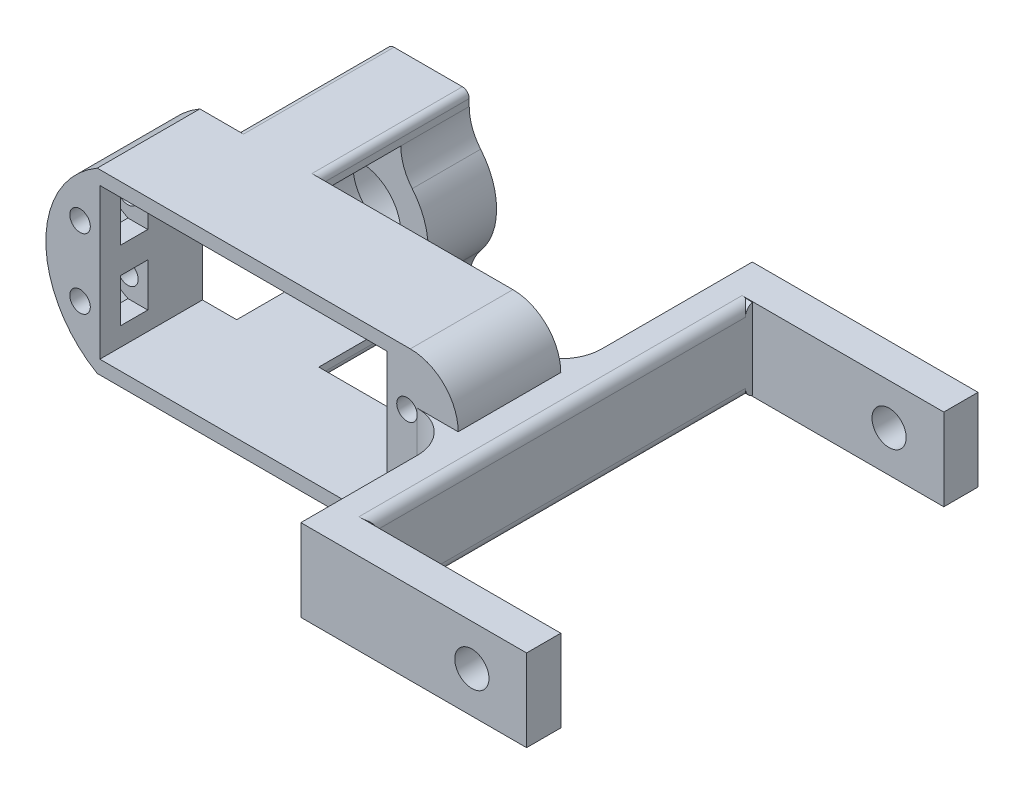
SolidWorks part; units mm, degrees
ref_plane "Plan de face" through (0, 0, 0) normal (0, 0, 1) x (1, 0, 0)
ref_plane "Plan de dessus" through (0, 0, 0) normal (0, 1, 0) x (1, 0, 0)
ref_plane "Plan de droite" through (0, 0, 0) normal (1, 0, 0) x (0, 0, -1)
sketch "Esquisse1" plane through (0, 0, 0) normal (0, 0, 1) x (1, 0, 0)
  line L1 (-23.2387, 9.5601) -> (56.7613, 9.5601)
  line L2 (-23.2387, 9.5601) -> (-23.2387, -16.4399)
  line L3 (-23.2387, -16.4399) -> (56.7613, -16.4399)
  line L4 (56.7613, 9.5601) -> (56.7613, -16.4399)
  dimension "D1" = 26
  dimension "D2" = 80
extrude "Boss.-Extru.1" add sketch "Esquisse1" along normal blind 5
sketch "Esquisse4" plane through (0, 0, 0) normal (0, 0, -1) x (-1, 0, 0)
  line L0 (23.2387, 9.5601) -> (23.2387, -16.4399) construction
  line L1 (38.2387, -13.9399) -> (23.2387, -13.9399)
  line L2 (38.2387, -13.9399) -> (38.2387, 7.0601)
  line L3 (38.2387, 7.0601) -> (23.2387, 7.0601)
  line L4 (23.2387, -13.9399) -> (23.2387, 7.0601)
  line L5 (23.2387, -16.4399) -> (-56.7613, -16.4399) construction
  line L6 (-56.7613, 9.5601) -> (23.2387, 9.5601) construction
  dimension "D1" = 0
  dimension "D2" = 2.5
  dimension "D3" = 2.5
  dimension "D4" = 15
extrude "Boss.-Extru.2" add sketch "Esquisse4" against normal blind 23
sketch "Esquisse6" plane through (0, -13.9399, 0) normal (0, -1, 0) x (1, 0, 0)
  line L0 (-23.2387, 23) -> (-23.2387, 5) construction
  line L1 (-23.2387, 0) -> (-38.2387, 0) construction
  circle A0 centre (-28.7387, 5) radius 1.9
  dimension "D2" = 5
  dimension "D3" = 3.8
  dimension "D1" = 5.5
extrude "Enlèv. mat.-Extru.1" cut sketch "Esquisse6" against normal blind 23
sketch "Esquisse7" plane through (0, 0, 23) normal (0, 0, 1) x (1, 0, 0)
  line L0 (-23.2387, 7.0601) -> (-23.2387, -13.9399) construction
  line L1 (-38.2387, 7.0601) -> (-23.2387, 7.0601) construction
  circle A0 centre (-33.2387, -3.4399) radius 2.5
  dimension "D1" = 5
  dimension "D2" = 10
  dimension "D3" = 10.5
extrude "Enlèv. mat.-Extru.2" cut sketch "Esquisse7" against normal blind 33
sketch "Esquisse8" plane through (0, 0, 0) normal (0, 0, -1) x (-1, 0, 0)
  line L0 (23.2387, -13.9399) -> (38.2387, -13.9399) construction
  line L1 (50.0831, -10.9399) -> (26.2387, -10.9399)
  line L2 (50.0831, -10.9399) -> (50.0831, 4.0601)
  line L3 (50.0831, 4.0601) -> (26.2387, 4.0601)
  line L4 (26.2387, -10.9399) -> (26.2387, 4.0601)
  line L5 (38.2387, 7.0601) -> (23.2387, 7.0601) construction
  line L6 (23.2387, -13.9399) -> (23.2387, -16.4399) construction
  dimension "D1" = 3
  dimension "D2" = 3
  dimension "D3" = 3
extrude "Enlèv. mat.-Extru.3" cut sketch "Esquisse8" against normal blind 20
sketch "Esquisse9" plane through (0, 0, 0) normal (0, 0, -1) x (-1, 0, 0)
  line L19 (38.2387, -13.9399) -> (38.2387, -10.9399)
  line L20 (38.2387, -10.9399) -> (26.2387, -10.9399)
  line L21 (26.2387, -10.9399) -> (26.2387, 4.0601)
  line L22 (26.2387, 4.0601) -> (38.2387, 4.0601)
  line L23 (38.2387, 4.0601) -> (38.2387, 7.0601)
  line L24 (38.2387, 7.0601) -> (23.2387, 7.0601)
  line L25 (23.2387, 7.0601) -> (23.2387, 9.5601)
  line L26 (23.2387, 9.5601) -> (-56.7613, 9.5601)
  line L27 (-56.7613, 9.5601) -> (-56.7613, -16.4399)
  line L28 (-56.7613, -16.4399) -> (23.2387, -16.4399)
  line L29 (23.2387, -16.4399) -> (23.2387, -13.9399)
  line L30 (23.2387, -13.9399) -> (38.2387, -13.9399)
  line L37 (23.2387, 7.0601) -> (23.2387, 9.5601)
  line L38 (23.2387, 9.5601) -> (17.8135, 9.5601)
  line L40 (17.8135, -16.4399) -> (23.2387, -16.4399)
  line L41 (23.2387, -16.4399) -> (23.2387, -13.9399)
  arc A3 (17.8135, -16.4399) -> (23.2387, -13.9399) centre (17.8135, -9.3033) ccw
  arc A4 (17.8135, 9.5601) -> (23.2387, 7.0601) centre (17.8135, 2.4236) cw
  dimension "D1" = 0
extrude "Enlèv. mat.-Extru.4" cut sketch "Esquisse9" against normal blind 20
sketch "Esquisse10" plane through (0, -13.9399, 0) normal (0, -1, 0) x (1, 0, 0)
  line L5 (-38.2387, 0) -> (-23.2387, 0)
  line L6 (-23.2387, 0) -> (-23.2387, 5)
  line L7 (-23.2387, 5) -> (-23.2387, 23)
  line L8 (-23.2387, 23) -> (-38.2387, 23)
  line L9 (-38.2387, 23) -> (-38.2387, 0)
  line L12 (-23.2387, 21.5) -> (-23.2387, 23)
  line L13 (-23.2387, 23) -> (-24.7387, 23)
  arc A0 (-23.2387, 21.5) -> (-24.7387, 23) centre (-24.7387, 21.5) ccw
  dimension "D2" = 3
  dimension "D1" = 0
extrude "Enlèv. mat.-Extru.5" cut sketch "Esquisse10" against normal blind 25
sketch "Esquisse12" plane through (0, -13.9399, 0) normal (0, -1, 0) x (1, 0, 0)
  line L0 (-24.7387, 23) -> (-38.2387, 23) construction
  line L1 (-38.2387, 23) -> (-36.7387, 23)
  line L2 (-38.2387, 23) -> (-38.2387, 21.5)
  arc A0 (-36.7387, 23) -> (-38.2387, 21.5) centre (-36.7387, 21.5) ccw
  dimension "D1" = 3
  dimension "D3" = 1.5
extrude "Enlèv. mat.-Extru.7" cut sketch "Esquisse12" against normal blind 25
sketch "Esquisse13" plane through (0, 7.0601, 0) normal (0, 1, 0) x (1, 0, 0)
  line L1 (-30.7594, -1.5) -> (-32.7801, -5)
  line L2 (-32.7801, -5) -> (-30.7594, -8.5)
  line L3 (-30.7594, -8.5) -> (-26.718, -8.5)
  line L4 (-26.718, -8.5) -> (-24.6972, -5)
  line L5 (-24.6972, -5) -> (-26.718, -1.5)
  line L6 (-26.718, -1.5) -> (-30.7594, -1.5)
  circle A0 centre (-28.7387, -5) radius 3.5 construction
  circle A1 centre (-28.7387, -5) radius 1.9 construction
  dimension "D1" = 7
extrude "Enlèv. mat.-Extru.8" cut sketch "Esquisse13" against normal blind 1
sketch "Esquisse14" plane through (0, 7.0601, 0) normal (0, 1, 0) x (1, 0, 0)
  line L0 (-30.7594, -1.5) -> (-32.7801, -5) construction
  line L1 (-26.718, -1.5) -> (-30.7594, -1.5) construction
  line L2 (-24.6972, -5) -> (-26.718, -1.5) construction
  line L3 (-26.718, -8.5) -> (-24.6972, -5) construction
  line L4 (-30.7594, -8.5) -> (-26.718, -8.5) construction
  line L6 (-25.8519, 0) -> (-31.6254, 0)
  line L7 (-31.6254, 0) -> (-34.5122, -5)
  line L8 (-34.5122, -5) -> (-31.6254, -10)
  line L9 (-31.6254, -10) -> (-25.8519, -10)
  line L15 (-32.7801, -5) -> (-30.7594, -8.5) construction
  line L16 (-30.7594, -1.5) -> (-32.7801, -5)
  line L17 (-26.718, -1.5) -> (-30.7594, -1.5)
  line L18 (-24.6972, -5) -> (-26.718, -1.5)
  line L19 (-26.718, -8.5) -> (-24.6972, -5)
  line L20 (-30.7594, -8.5) -> (-26.718, -8.5)
  line L21 (-32.7801, -5) -> (-30.7594, -8.5)
  line L22 (-25.8519, -10) -> (-23.2387, -5.4737)
  line L27 (-23.2387, -4.5263) -> (-25.8519, 0)
  line L28 (-38.2387, 0) -> (-23.2387, 0) construction
  line L29 (-23.2387, -4.5263) -> (-23.2387, -5.4737)
  line L30 (-23.2387, -21.5) -> (-23.2387, -5) construction
  circle A1 centre (-28.7387, -5) radius 5 construction
  circle A2 centre (-28.7387, -5) radius 1.9 construction
extrude "Boss.-Extru.3" add sketch "Esquisse14" along normal blind 2
sketch "Esquisse15" plane through (0, 0, 0) normal (0, 0, -1) x (-1, 0, 0)
  circle A7 centre (-51.7613, -8.5399) radius 1.5
  circle A8 centre (-51.7613, 1.6601) radius 1.5
  circle A9 centre (-3.9613, -8.5399) radius 1.5
  circle A10 centre (-3.9613, 1.6601) radius 1.5
  dimension "D10" = 3
extrude "Enlèv. mat.-Extru.9" cut sketch "Esquisse15" against normal blind 19
sketch "Esquisse16" plane through (0, 0, 0) normal (0, 0, -1) x (-1, 0, 0)
  line L0 (17.8135, -16.4399) -> (-56.7613, -16.4399) construction
  line L1 (-56.7613, -16.4399) -> (-56.7613, 9.5601) construction
  line L2 (-43.3764, 11.4729) -> (-43.3764, 11.5601)
  line L3 (-43.3764, -43.1341) -> (-70.7923, -43.1341)
  line L4 (-43.3764, -43.1341) -> (-43.3764, -18.3527)
  line L5 (-43.3764, 11.5601) -> (-70.7923, 11.5601)
  line L6 (-70.7923, -43.1341) -> (-70.7923, 11.5601)
  arc A0 (-43.3764, 11.4729) -> (-43.3764, -18.3527) centre (-41.7613, -3.4399) ccw
  dimension "D1" = 13
  dimension "D2" = 30
  dimension "D3" = 15
extrude "Enlèv. mat.-Extru.10" cut sketch "Esquisse16" against normal blind 19
sketch "Esquisse17" plane through (0, 0, 5) normal (0, 0, 1) x (1, 0, 0)
  line L0 (49.2446, 9.5601) -> (-17.8135, 9.5601) construction
  line L1 (6.8613, 7.5601) -> (48.8613, 7.5601)
  line L2 (6.8613, 7.5601) -> (6.8613, -14.4399)
  line L3 (6.8613, -14.4399) -> (48.8613, -14.4399)
  line L4 (48.8613, 7.5601) -> (48.8613, -14.4399)
  circle A0 centre (3.9613, 1.6601) radius 1.5 construction
  dimension "D4" = 2.9
  dimension "D1" = 42
  dimension "D2" = 22
  dimension "D3" = 2
extrude "Enlèv. mat.-Extru.11" cut sketch "Esquisse17" against normal blind 19
sketch "Esquisse18" plane through (0, 0, 0) normal (0, 0, -1) x (-1, 0, 0)
  line L13 (-49.0113, 3.2479) -> (-51.7613, 4.8356)
  line L14 (-51.7613, 4.8356) -> (-54.5113, 3.2479)
  line L15 (-54.5113, 3.2479) -> (-54.5113, 0.0724)
  line L16 (-54.5113, 0.0724) -> (-51.7613, -1.5153)
  line L17 (-51.7613, -1.5153) -> (-49.0113, 0.0724)
  line L19 (-49.0113, -6.9521) -> (-51.7613, -5.3644)
  line L20 (-51.7613, -5.3644) -> (-54.5113, -6.9521)
  line L21 (-54.5113, -6.9521) -> (-54.5113, -10.1276)
  line L22 (-54.5113, -10.1276) -> (-51.7613, -11.7153)
  line L23 (-51.7613, -11.7153) -> (-49.0113, -10.1276)
  line L25 (-49.0113, -10.1276) -> (-46.2613, -8.5399)
  line L26 (-46.2613, -8.5399) -> (-49.0113, -6.9521)
  line L28 (-49.0113, 3.2479) -> (-46.2613, 1.6601)
  line L29 (-49.0113, 0.0724) -> (-46.2613, 1.6601)
  line L30 (-49.0113, -10.1276) -> (-49.0113, -8.5399) [skipped]
  line L31 (-49.0113, 0.0724) -> (-49.0113, 1.6601) [skipped]
  line L33 (-6.7113, 0.0724) -> (-9.4613, 1.6601)
  line L34 (-6.7113, 3.2479) -> (-9.4613, 1.6601)
  line L35 (-9.4613, -8.5399) -> (-6.7113, -6.9521)
  line L36 (-6.7113, -10.1276) -> (-9.4613, -8.5399)
  line L37 (-3.9613, -11.7153) -> (-6.7113, -10.1276)
  line L38 (-1.2113, -10.1276) -> (-3.9613, -11.7153)
  line L39 (-1.2113, -6.9521) -> (-1.2113, -10.1276)
  line L40 (-3.9613, -5.3644) -> (-1.2113, -6.9521)
  line L41 (-6.7113, -6.9521) -> (-3.9613, -5.3644)
  line L42 (-3.9613, -1.5153) -> (-6.7113, 0.0724)
  line L43 (-1.2113, 0.0724) -> (-3.9613, -1.5153)
  line L44 (-1.2113, 3.2479) -> (-1.2113, 0.0724)
  line L45 (-3.9613, 4.8356) -> (-1.2113, 3.2479)
  line L46 (-6.7113, 3.2479) -> (-3.9613, 4.8356)
  arc A0 (-5.3363, -6.1583) -> (-5.3363, -10.9214) centre (-3.9613, -8.5399) cw construction
  arc A1 (-5.3363, 4.0417) -> (-5.3363, -0.7214) centre (-3.9613, 1.6601) cw construction
  arc A2 (-50.3863, 4.0417) -> (-50.3863, -0.7214) centre (-51.7613, 1.6601) ccw construction
  arc A3 (-50.3863, -6.1583) -> (-50.3863, -10.9214) centre (-51.7613, -8.5399) ccw construction
  circle A6 centre (-51.7613, 1.6601) radius 1.5 construction
  circle A7 centre (-51.7613, -8.5399) radius 1.5 construction
  dimension "D1" = 5.5
  dimension "D2" = 5.5
extrude "Enlèv. mat.-Extru.12" cut sketch "Esquisse18" against normal blind 2
sketch "Esquisse19" plane through (0, 0, 0) normal (0, 0, -1) x (-1, 0, 0)
  line L9 (-12.8613, -16.4399) -> (-22.8613, -16.4399)
  line L12 (-11.8613, -15.4399) -> (-11.8613, -14.4399)
  line L13 (-11.8613, -14.4399) -> (-23.8613, -14.4399)
  line L21 (-23.8613, -15.4399) -> (-23.8613, -14.4399)
  line L22 (-6.8613, -10.041) -> (-6.8613, -14.4399) construction
  line L23 (-6.8613, -14.4399) -> (-48.8613, -14.4399) construction
  line L24 (17.8135, -16.4399) -> (-49.2446, -16.4399) construction
  line L27 (-23.8613, 8.5601) -> (-23.8613, 7.5601)
  line L28 (-11.8613, 7.5601) -> (-23.8613, 7.5601)
  line L29 (-11.8613, 8.5601) -> (-11.8613, 7.5601)
  line L30 (-12.8613, 9.5601) -> (-22.8613, 9.5601)
  arc A2 (-12.8613, -16.4399) -> (-11.8613, -15.4399) centre (-12.8613, -15.4399) ccw
  arc A3 (-23.8613, -15.4399) -> (-22.8613, -16.4399) centre (-22.8613, -15.4399) ccw
  arc A6 (-23.8613, 8.5601) -> (-22.8613, 9.5601) centre (-22.8613, 8.5601) cw
  arc A7 (-12.8613, 9.5601) -> (-11.8613, 8.5601) centre (-12.8613, 8.5601) cw
  point P4 (-17.8613, -16.4399)
  dimension "D3" = 0
  dimension "D4" = 0
  dimension "D5" = 2
  dimension "D1" = 10
  dimension "D2" = 11
  dimension "D6" = 2
extrude "Boss.-Extru.4" add sketch "Esquisse19" along normal blind 22
sketch "Esquisse23" plane through (0, 0, -22) normal (0, 0, -1) x (-1, 0, 0)
  line L0 (-6.8613, -10.041) -> (-6.8613, -14.4399) construction
  line L4 (-23.8613, 8.5601) -> (-23.8613, 7.5601)
  line L5 (-23.8613, 7.5601) -> (-11.8613, 7.5601)
  line L6 (-11.8613, 7.5601) -> (-11.8613, 8.5601)
  line L7 (-12.8613, 9.5601) -> (-22.8613, 9.5601)
  line L8 (-23.8613, 8.5601) -> (-23.8613, 7.5601)
  line L10 (-11.8613, 7.5601) -> (-11.8613, 8.5601)
  line L11 (-12.8613, 9.5601) -> (-22.8613, 9.5601)
  line L12 (-22.8613, -16.4399) -> (-12.8613, -16.4399)
  line L13 (-11.8613, -15.4399) -> (-11.8613, -14.4399)
  line L14 (-11.8613, -14.4399) -> (-23.8613, -14.4399)
  line L15 (-23.8613, -14.4399) -> (-23.8613, -15.4399)
  line L16 (-22.8613, -16.4399) -> (-12.8613, -16.4399)
  line L17 (-11.8613, -15.4399) -> (-11.8613, -14.4399)
  line L19 (-23.8613, -14.4399) -> (-23.8613, -15.4399)
  line L21 (-6.8613, -14.4399) -> (-11.8613, -14.4399) construction
  arc A0 (-10.1971, -9.8632) -> (-10.1971, 2.9835) centre (-17.8613, -3.4399) ccw
  arc A1 (-11.8613, 7.5601) -> (-10.1971, 2.9835) centre (-4.7363, 7.5601) ccw
  arc A2 (-22.8613, 9.5601) -> (-23.8613, 8.5601) centre (-22.8613, 8.5601) ccw
  arc A3 (-11.8613, 8.5601) -> (-12.8613, 9.5601) centre (-12.8613, 8.5601) ccw
  arc A4 (-22.8613, 9.5601) -> (-23.8613, 8.5601) centre (-22.8613, 8.5601) ccw
  arc A5 (-11.8613, 8.5601) -> (-12.8613, 9.5601) centre (-12.8613, 8.5601) ccw
  arc A6 (-23.8613, -15.4399) -> (-22.8613, -16.4399) centre (-22.8613, -15.4399) ccw
  arc A7 (-12.8613, -16.4399) -> (-11.8613, -15.4399) centre (-12.8613, -15.4399) ccw
  arc A8 (-23.8613, -15.4399) -> (-22.8613, -16.4399) centre (-22.8613, -15.4399) ccw
  arc A9 (-12.8613, -16.4399) -> (-11.8613, -15.4399) centre (-12.8613, -15.4399) ccw
  arc A10 (-23.8613, 7.5601) -> (-25.5255, 2.9835) centre (-30.9863, 7.5601) cw
  arc A11 (-23.8613, -14.4399) -> (-25.5255, -9.8632) centre (-30.9863, -14.4399) ccw
  arc A12 (-11.8613, -14.4399) -> (-10.1971, -9.8632) centre (-4.7363, -14.4399) cw
  arc A13 (-25.5255, 2.9835) -> (-25.5255, -9.8632) centre (-17.8613, -3.4399) ccw
  dimension "D3" = 20
  dimension "D5" = 11
  dimension "D4" = 11
  dimension "D1" = 0
  dimension "D2" = 0
extrude "Boss.-Extru.5" add sketch "Esquisse23" along normal blind 10
sketch "Esquisse25" plane through (0, 0, -32) normal (0, 0, -1) x (-1, 0, 0)
  circle A0 centre (-17.8613, -3.4399) radius 8
  arc A1 (-10.1971, -9.8632) -> (-10.1971, 2.9835) centre (-17.8613, -3.4399) ccw construction
  dimension "D1" = 16
extrude "Enlèv. mat.-Extru.13" cut sketch "Esquisse25" against normal blind 5
sketch "Esquisse26" plane through (0, 0, -27) normal (0, 0, -1) x (-1, 0, 0)
  circle A0 centre (-17.8613, -3.4399) radius 6
  circle A1 centre (-17.8613, -3.4399) radius 8 construction
  dimension "D1" = 12
extrude "Enlèv. mat.-Extru.14" cut sketch "Esquisse26" against normal blind 5
sketch "Esquisse29" plane through (0, -13.9399, 0) normal (0, -1, 0) x (1, 0, 0)
  line L0 (-23.2387, 0) -> (-38.2387, 0) construction
  line L1 (-26.718, 1.5) -> (-24.6972, 5)
  line L2 (-24.6972, 5) -> (-26.718, 8.5)
  line L3 (-26.718, 8.5) -> (-30.7594, 8.5)
  line L4 (-30.7594, 8.5) -> (-32.7801, 5)
  line L5 (-32.7801, 5) -> (-30.7594, 1.5)
  line L6 (-30.7594, 1.5) -> (-26.718, 1.5)
  circle A0 centre (-28.7387, 5) radius 3.5 construction
  circle A1 centre (-28.7387, 5) radius 1.9 construction
  dimension "D1" = 7
extrude "Enlèv. mat.-Extru.15" cut sketch "Esquisse29" against normal blind 1
sketch "Esquisse32" plane through (0, -13.9399, 0) normal (0, -1, 0) x (1, 0, 0)
  line L0 (-26.718, 8.5) -> (-30.7594, 8.5) construction
  line L1 (-25.8519, 0) -> (-23.2387, 4.5263)
  line L2 (-23.2387, 5.4737) -> (-25.8519, 10)
  line L3 (-25.8519, 10) -> (-31.6254, 10)
  line L4 (-31.6254, 10) -> (-34.5122, 5)
  line L5 (-34.5122, 5) -> (-31.6254, 0)
  line L6 (-31.6254, 0) -> (-25.8519, 0)
  line L7 (-26.718, 1.5) -> (-24.6972, 5)
  line L8 (-24.6972, 5) -> (-26.718, 8.5)
  line L9 (-26.718, 8.5) -> (-30.7594, 8.5)
  line L10 (-30.7594, 8.5) -> (-32.7801, 5)
  line L11 (-32.7801, 5) -> (-30.7594, 1.5)
  line L12 (-30.7594, 1.5) -> (-26.718, 1.5)
  line L13 (-23.2387, 0) -> (-38.2387, 0) construction
  line L14 (-23.2387, 5.4737) -> (-23.2387, 4.5263)
  line L15 (-23.2387, 21.5) -> (-23.2387, 5) construction
  circle A0 centre (-28.7387, 5) radius 5 construction
  circle A1 centre (-28.7387, 5) radius 3.5 construction
  circle A2 centre (-28.7387, 5) radius 1.9 construction
extrude "Boss.-Extru.6" add sketch "Esquisse32" along normal blind 2
sketch "Esquisse33" plane through (0, 0, 5) normal (0, 0, 1) x (1, 0, 0)
  line L1 (6.478, -16.4399) -> (-54.7028, -16.4399)
  line L3 (6.478, 9.5601) -> (-54.7028, 9.5601)
  line L4 (-54.7028, -16.4399) -> (-54.7028, 9.5601)
  arc A2 (6.478, -16.4399) -> (6.478, 9.5601) centre (13.9613, -3.4399) cw
extrude "Enlèv. mat.-Extru.16" cut sketch "Esquisse33" along normal blind 25 and the other way blind 25
sketch "Esquisse34" plane through (0, 0, 5) normal (0, 0, 1) x (1, 0, 0)
  line L1 (59.2446, -16.4399) -> (49.2446, -16.4399)
  line L2 (59.2446, -16.4399) -> (59.2446, 9.5601)
  line L3 (59.2446, 9.5601) -> (49.2446, 9.5601)
  arc A0 (49.2446, -16.4399) -> (49.2446, 9.5601) centre (41.7613, -3.4399) ccw construction
  arc A1 (49.2446, -16.4399) -> (49.2446, 9.5601) centre (41.7613, -3.4399) ccw
  dimension "D1" = 10
extrude "Boss.-Extru.7" add sketch "Esquisse34" against normal blind 5
sketch "Esquisse35" plane through (0, 0, 5) normal (0, 0, 1) x (1, 0, 0)
  line L1 (62.7446, -9.4399) -> (59.2446, -9.4399)
  line L2 (64.2446, -7.9399) -> (64.2446, 1.0601)
  line L3 (62.7446, 2.5601) -> (59.2446, 2.5601)
  line L4 (59.2446, -9.4399) -> (59.2446, 2.5601)
  line L5 (48.8613, 7.5601) -> (6.8613, 7.5601) construction
  line L6 (59.2446, -16.4399) -> (59.2446, 9.5601) construction
  arc A0 (62.7446, -9.4399) -> (64.2446, -7.9399) centre (62.7446, -7.9399) ccw
  arc A1 (64.2446, 1.0601) -> (62.7446, 2.5601) centre (62.7446, 1.0601) ccw
  point P4 (59.2446, -3.4399)
  dimension "D5" = 3
  dimension "D6" = 1.5
  dimension "D7" = 1.5
  dimension "D8" = 1.5
  dimension "D9" = 1.5
  dimension "D10" = 3
  dimension "D1" = 12
  dimension "D2" = 11
  dimension "D3" = 0
extrude "Boss.-Extru.8" add sketch "Esquisse35" against normal blind 43 and the other way blind 23
sketch "Esquisse36" plane through (64.2446, 0, 0) normal (1, 0, 0) x (0, 0, -1)
  line L0 (-28, -9.4399) -> (38, -9.4399) construction
  line L1 (33.5, 2.5601) -> (38, 2.5601)
  line L2 (32, 1.0601) -> (32, -7.9399)
  line L3 (33.5, -9.4399) -> (38, -9.4399)
  line L4 (38, 2.5601) -> (38, -9.4399)
  line L5 (-28, 2.5601) -> (38, 2.5601) construction
  line L6 (38, -7.9399) -> (38, 1.0601) construction
  line L10 (-28, 2.5601) -> (-28, -9.4399)
  line L11 (-23.5, -9.4399) -> (-28, -9.4399)
  line L12 (-22, 1.0601) -> (-22, -7.9399)
  line L13 (-23.5, 2.5601) -> (-28, 2.5601)
  arc A0 (32, -7.9399) -> (33.5, -9.4399) centre (33.5, -7.9399) ccw
  arc A1 (33.5, 2.5601) -> (32, 1.0601) centre (33.5, 1.0601) ccw
  arc A2 (-23.5, 2.5601) -> (-22, 1.0601) centre (-23.5, 1.0601) cw
  arc A3 (-22, -7.9399) -> (-23.5, -9.4399) centre (-23.5, -7.9399) cw
  dimension "D2" = 3
  dimension "D3" = 3
extrude "Boss.-Extru.10" add sketch "Esquisse36" along normal blind 45 and the other way blind 3
sketch "Esquisse39" plane through (0, 0, -38) normal (0, 0, -1) x (-1, 0, 0)
  line L1 (-109.2446, 2.5601) -> (-59.2446, 2.5601) construction
  line L2 (-109.2446, -9.4399) -> (-109.2446, 2.5601) construction
  line L4 (-77.7127, 2.5601) -> (-100.2936, 2.5601)
  line L5 (-77.7127, 2.5601) -> (-77.7127, -9.4399)
  line L6 (-77.7127, -9.4399) -> (-100.2936, -9.4399)
  arc A0 (-101.4627, -1.5845) -> (-101.4627, -5.2952) centre (-109.2446, -3.4399) ccw
  spline S0 degree 3 poles (-101.4627, -5.2952) (-99.2241, -4.6117) (-102.4654, -9.859) (-100.2936, -9.4399) knots 0 0 0 0 0.141371 0.141371 0.141371 0.141371
  spline S1 degree 3 poles (-101.4627, -1.5845) (-99.2241, -2.268) (-102.4654, 2.9793) (-100.2936, 2.5601) knots 0 0 0 0 0.141371 0.141371 0.141371 0.141371
  dimension "D1" = 16
  dimension "D2" = 6
  dimension "D3" = 0
  dimension "D6" = 0
extrude "Boss.-Extru.12" add sketch "Esquisse39" against normal blind 5
sketch "Esquisse40" plane through (109.2446, 0, 0) normal (1, 0, 0) x (0, 0, -1)
  line L2 (33, -9.3541) -> (33, 2.4744)
  line L3 (32, 1.0601) -> (32, -7.9399)
  line L5 (32, 1.0601) -> (32, -7.9399)
  line L6 (33, -9.3541) -> (33, 2.4744)
  arc A2 (32, -7.9399) -> (33, -9.3541) centre (33.5, -7.9399) ccw
  arc A3 (33, 2.4744) -> (32, 1.0601) centre (33.5, 1.0601) ccw
  arc A4 (32, -7.9399) -> (33, -9.3541) centre (33.5, -7.9399) ccw
  arc A5 (33, 2.4744) -> (32, 1.0601) centre (33.5, 1.0601) ccw
  dimension "D1" = 0
extrude "Enlèv. mat.-Extru.18" cut sketch "Esquisse40" against normal blind 45
sketch "Esquisse41" plane through (59.2446, 0, 0) normal (-1, 0, 0) x (0, 0, 1)
  line L0 (0, 2.5601) -> (-38, 2.5601) construction
  line L1 (-38, -9.4399) -> (-33, -9.4399)
  line L2 (-38, -9.4399) -> (-38, 2.5601)
  line L3 (-38, 2.5601) -> (-33, 2.5601)
  line L4 (-33, -9.4399) -> (-33, 2.5601)
  line L5 (-38, 2.5601) -> (-38, -9.4399) construction
  line L6 (0, -9.4399) -> (-38, -9.4399) construction
  dimension "D1" = 5
extrude "Boss.-Extru.13" add sketch "Esquisse41" against normal blind 37
sketch "Esquisse42" plane through (0, 0, -33) normal (0, 0, 1) x (1, 0, 0)
  line L1 (105.7446, -5.4606) -> (109.2446, -7.4813)
  line L2 (109.2446, -7.4813) -> (112.7446, -5.4606)
  line L3 (112.7446, -5.4606) -> (112.7446, -1.4191)
  line L4 (112.7446, -1.4191) -> (109.2446, 0.6016)
  line L5 (109.2446, 0.6016) -> (105.7446, -1.4191)
  line L6 (105.7446, -1.4191) -> (105.7446, -5.4606)
  circle A0 centre (109.2446, -3.4399) radius 3.5 construction
  arc A1 (103.8574, -9.3541) -> (103.8574, 2.4744) centre (109.2446, -3.4399) ccw construction
  dimension "D1" = 7
extrude "Enlèv. mat.-Extru.19" cut sketch "Esquisse42" against normal blind 2
sketch "Esquisse43" plane through (0, 0, -38) normal (0, 0, -1) x (-1, 0, 0)
  circle A0 centre (-109.2446, -3.4399) radius 2
  arc A2 (-103.9531, 2.5601) -> (-103.9531, -9.4399) centre (-109.2446, -3.4399) ccw construction
  dimension "D1" = 4
extrude "Enlèv. mat.-Extru.20" cut sketch "Esquisse43" against normal blind 18
sketch "Esquisse44" plane through (0, 0, 28) normal (0, 0, 1) x (1, 0, 0)
  line L1 (117.9958, 12.8483) -> (93.3939, 12.8483)
  line L2 (117.9958, 12.8483) -> (117.9958, -24.309)
  line L3 (117.9958, -24.309) -> (93.3939, -24.309)
  line L4 (93.3939, 12.8483) -> (93.3939, -24.309)
extrude "Enlèv. mat.-Extru.21" cut sketch "Esquisse44" against normal blind 18
sketch "Esquisse45" plane through (0, 0, 28) normal (0, 0, 1) x (1, 0, 0)
  line L5 (100.2936, 2.5601) -> (62.7446, 2.5601)
  line L6 (63.2446, 2.4744) -> (64.2446, 2.4744)
  line L7 (63.2446, 2.4744) -> (64.2446, 2.4744)
  line L8 (64.2446, 2.4744) -> (64.2446, -9.3541)
  line L9 (62.7446, -9.4399) -> (100.2936, -9.4399)
  line L10 (100.2936, 2.5601) -> (62.7446, 2.5601)
  line L14 (62.7446, -9.4399) -> (100.2936, -9.4399)
  line L16 (64.2446, 2.4744) -> (64.2446, -9.3541)
  line L17 (64.2446, -9.3541) -> (63.2446, -9.3541)
  line L18 (64.2446, -9.3541) -> (63.2446, -9.3541)
  line L19 (100.8756, -9.3541) -> (103.8574, -9.3541)
  line L20 (100.8756, -9.3541) -> (103.8574, -9.3541)
  line L22 (103.8574, 2.4744) -> (100.8756, 2.4744)
  line L23 (103.8574, 2.4744) -> (100.8756, 2.4744)
  circle A0 centre (109.2446, -3.4399) radius 1.5
  circle A1 centre (109.2446, -3.4399) radius 2 construction
  circle A2 centre (98.8946, -3.4399) radius 1
  arc A7 (63.2446, 2.4744) -> (62.7446, 2.5601) centre (62.7446, 1.0601) ccw
  arc A8 (62.7446, -9.4399) -> (63.2446, -9.3541) centre (62.7446, -7.9399) ccw
  arc A9 (103.8574, -9.3541) -> (103.8574, 2.4744) centre (109.2446, -3.4399) ccw
  arc A10 (63.2446, 2.4744) -> (62.7446, 2.5601) centre (62.7446, 1.0601) ccw
  arc A11 (62.7446, -9.4399) -> (63.2446, -9.3541) centre (62.7446, -7.9399) ccw
  arc A13 (103.8574, -9.3541) -> (103.8574, 2.4744) centre (109.2446, -3.4399) ccw
  spline S2 degree 3 poles (1480.9523, 1449.9641) (-1291.4609, -1493.434) (1494.9879, 1491.3216) (-1284.6297, -1440.1608) knots -0.763957 -0.763957 -0.763957 -0.763957 0.65972 0.65972 0.65972 0.65972 only from (100.8756, 2.4744) to (100.2936, 2.5601)
  spline S3 degree 3 poles (-1284.6645, 1433.3177) (1494.9978, -1498.2122) (-1291.4458, 1486.5379) (1480.9124, -1456.8015) knots -0.518355 -0.518355 -0.518355 -0.518355 0.905321 0.905321 0.905321 0.905321 only from (100.2936, -9.4399) to (100.8756, -9.3541)
  spline S4 degree 3 poles (100.8756, 2.4744) (100.752, 2.5764) (100.5651, 2.6125) (100.2936, 2.5601) knots 0 0 0 0 0.017672 0.017672 0.017672 0.017672
  spline S5 degree 3 poles (100.2936, -9.4399) (100.5651, -9.4923) (100.752, -9.4561) (100.8756, -9.3541) knots 0.123699 0.123699 0.123699 0.123699 0.141371 0.141371 0.141371 0.141371
  dimension "D1" = 3
  dimension "D2" = 2
  dimension "D3" = 0
  dimension "D4" = 10.35
  dimension "D5" = 0
extrude "Boss.-Extru.14" add sketch "Esquisse45" against normal blind 5
sketch "Esquisse46" plane through (93.3939, 0, 0) normal (1, 0, 0) x (0, 0, -1)
  line L2 (-23, 2.4744) -> (-23, -9.3541)
  line L3 (-22, -7.9399) -> (-22, 1.0601)
  line L4 (-23, 2.4744) -> (-23, -9.3541)
  line L5 (-22, -7.9399) -> (-22, 1.0601)
  arc A2 (-23, -9.3541) -> (-22, -7.9399) centre (-23.5, -7.9399) ccw
  arc A3 (-22, 1.0601) -> (-23, 2.4744) centre (-23.5, 1.0601) ccw
  arc A4 (-23, -9.3541) -> (-22, -7.9399) centre (-23.5, -7.9399) ccw
  arc A5 (-22, 1.0601) -> (-23, 2.4744) centre (-23.5, 1.0601) ccw
  dimension "D1" = 0
extrude "Enlèv. mat.-Extru.22" cut sketch "Esquisse46" against normal blind 29
sketch "Esquisse47" plane through (0, 0, 22) normal (0, 0, -1) x (-1, 0, 0)
  line L4 (-64.2446, 1.0601) -> (-64.3939, 1.0601)
  line L5 (-64.3939, 1.0601) -> (-64.3939, -7.9399)
  line L6 (-64.3939, -7.9399) -> (-64.2446, -7.9399)
  line L7 (-64.2446, -7.9399) -> (-64.2446, 1.0601)
  line L8 (-64.2446, 1.0601) -> (-64.3939, 1.0601)
  line L9 (-64.3939, 1.0601) -> (-64.3939, -7.9399)
  line L10 (-64.3939, -7.9399) -> (-64.2446, -7.9399)
  line L11 (-64.2446, -7.9399) -> (-64.2446, 1.0601)
  dimension "D1" = 0
extrude "Enlèv. mat.-Extru.23" cut sketch "Esquisse47" against normal blind 1
sketch "Esquisse48" plane through (0, 1.0601, 0) normal (0, -1, 0) x (1, 0, 0)
  line L4 (64.2446, 22) -> (64.3939, 22)
  line L5 (64.3939, 22) -> (64.3939, 23)
  line L6 (64.3939, 23) -> (64.2446, 23)
  line L7 (64.2446, 23) -> (64.2446, 22)
  line L8 (64.2446, 22) -> (64.3939, 22)
  line L9 (64.3939, 22) -> (64.3939, 23)
  line L10 (64.3939, 23) -> (64.2446, 23)
  line L11 (64.2446, 23) -> (64.2446, 22)
  dimension "D1" = 0
extrude "Enlèv. mat.-Extru.24" cut sketch "Esquisse48" along normal blind 21 and the other way blind 15
sketch "Esquisse49" plane through (0, 0, 5) normal (0, 0, 1) x (1, 0, 0)
  line L1 (59.2446, 9.5601) -> (6.478, 9.5601) construction
  line L2 (59.2446, -16.4399) -> (59.2446, -9.4399) construction
  line L3 (6.478, -16.4399) -> (59.2446, -16.4399) construction
  line L4 (59.2446, -9.4399) -> (59.2446, -16.4399)
  line L5 (59.2446, 9.5601) -> (52.2446, 9.5601)
  line L6 (59.2446, 9.5601) -> (59.2446, 2.5601)
  line L7 (59.2446, -16.4399) -> (52.2446, -16.4399)
  arc A2 (59.2446, 2.5601) -> (52.2446, 9.5601) centre (52.2446, 2.5601) ccw
  arc A3 (52.2446, -16.4399) -> (59.2446, -9.4399) centre (52.2446, -9.4399) ccw
extrude "Enlèv. mat.-Extru.25" cut sketch "Esquisse49" against normal blind 21
sketch "Esquisse50" plane through (0, 2.5601, 0) normal (0, 1, 0) x (1, 0, 0)
  line L0 (59.2446, -28) -> (59.2446, -5) construction
  line L1 (52.2446, -5) -> (59.2446, -5) construction
  line L4 (59.2446, 5.9833) -> (59.2446, -10.9833)
  line L9 (53.2613, 0) -> (53.2613, -5)
  arc A0 (59.2446, -10.9833) -> (53.2613, -5) centre (53.2613, -10.9833) ccw
  arc A2 (59.2446, 5.9833) -> (53.2613, 0) centre (53.2613, 5.9833) cw
extrude "Boss.-Extru.15" add sketch "Esquisse50" against normal blind 12
sketch "Esquisse51" plane through (0, 0, 0) normal (0, 0, -1) x (-1, 0, 0)
  line L0 (-51.7613, 4.8356) -> (-54.5113, 3.2479) construction
  line L1 (-49.0113, -10.1276) -> (-49.0113, -6.9521)
  line L2 (-49.0113, -6.9521) -> (-51.7613, -5.3644)
  line L3 (-51.7613, -5.3644) -> (-54.5113, -6.9521)
  line L4 (-54.5113, -6.9521) -> (-54.5113, -10.1276)
  line L5 (-54.5113, -10.1276) -> (-51.7613, -11.7153)
  line L6 (-51.7613, -11.7153) -> (-49.0113, -10.1276)
  line L7 (-49.0113, 3.2479) -> (-51.7613, 4.8356)
  line L8 (-51.7613, 4.8356) -> (-54.5113, 3.2479)
  line L9 (-54.5113, 3.2479) -> (-54.5113, 0.0724)
  line L10 (-54.5113, 0.0724) -> (-51.7613, -1.5153)
  line L11 (-51.7613, -1.5153) -> (-49.0113, 0.0724)
  line L12 (-49.0113, 0.0724) -> (-49.0113, 3.2479)
  line L13 (-54.5113, -9.4399) -> (-54.5113, -10.1276) construction
  circle A0 centre (-51.7613, -8.5399) radius 2.75 construction
  circle A1 centre (-51.7613, 1.6601) radius 2.75 construction
  circle A2 centre (-51.7613, 1.6601) radius 1.5 construction
  circle A3 centre (-51.7613, -8.5399) radius 1.5 construction
extrude "Enlèv. mat.-Extru.26" cut sketch "Esquisse51" against normal blind 2 and the other way blind 13
sketch "Esquisse52" plane through (0, 0, 0) normal (0, 0, -1) x (-1, 0, 0)
  line L6 (-51.7613, -1.5153) -> (-53.2613, -0.6493)
  line L7 (-53.2613, -0.6493) -> (-53.2613, -6.2305)
  line L8 (-59.2446, 2.5601) -> (-54.5113, 2.5601)
  line L9 (-54.5113, 2.5601) -> (-54.5113, 3.2479)
  line L10 (-54.5113, 3.2479) -> (-51.7613, 4.8356)
  line L11 (-51.7613, 4.8356) -> (-48.8613, 3.1612)
  line L12 (-48.8613, 3.1612) -> (-48.8613, 7.5601)
  line L13 (-48.8613, 7.5601) -> (-23.8613, 7.5601)
  line L14 (-23.8613, 7.5601) -> (-23.8613, 8.5601)
  line L15 (-22.8613, 9.5601) -> (-52.2446, 9.5601)
  line L16 (-59.2446, 2.5601) -> (-54.5113, 2.5601)
  line L17 (-54.5113, 2.5601) -> (-54.5113, 3.2479)
  line L18 (-54.5113, 3.2479) -> (-51.7613, 4.8356)
  line L19 (-51.7613, 4.8356) -> (-48.8613, 3.1612)
  line L20 (-48.8613, 3.1612) -> (-48.8613, 7.5601)
  line L21 (-48.8613, 7.5601) -> (-23.8613, 7.5601)
  line L22 (-23.8613, 7.5601) -> (-23.8613, 8.5601)
  line L23 (-22.8613, 9.5601) -> (-52.2446, 9.5601)
  line L24 (-53.2613, -6.2305) -> (-51.7613, -5.3644)
  line L25 (-51.7613, -5.3644) -> (-48.8613, -7.0388)
  line L26 (-48.8613, -7.0388) -> (-48.8613, 0.159)
  line L27 (-48.8613, 0.159) -> (-51.7613, -1.5153)
  line L28 (-51.7613, -1.5153) -> (-53.2613, -0.6493)
  line L29 (-53.2613, -0.6493) -> (-53.2613, -6.2305)
  line L30 (-53.2613, -6.2305) -> (-51.7613, -5.3644)
  line L31 (-51.7613, -5.3644) -> (-48.8613, -7.0388)
  line L32 (-48.8613, -7.0388) -> (-48.8613, 0.159)
  line L33 (-48.8613, 0.159) -> (-51.7613, -1.5153)
  line L36 (-54.5113, -9.4399) -> (-59.2446, -9.4399)
  line L37 (-52.2446, -16.4399) -> (-22.8613, -16.4399)
  line L38 (-23.8613, -15.4399) -> (-23.8613, -14.4399)
  line L39 (-23.8613, -14.4399) -> (-48.8613, -14.4399)
  line L40 (-48.8613, -14.4399) -> (-48.8613, -10.041)
  line L41 (-48.8613, -10.041) -> (-51.7613, -11.7153)
  line L42 (-51.7613, -11.7153) -> (-54.5113, -10.1276)
  line L43 (-54.5113, -10.1276) -> (-54.5113, -9.4399)
  line L44 (-54.5113, -9.4399) -> (-59.2446, -9.4399)
  line L45 (-52.2446, -16.4399) -> (-22.8613, -16.4399)
  line L46 (-23.8613, -15.4399) -> (-23.8613, -14.4399)
  line L47 (-23.8613, -14.4399) -> (-48.8613, -14.4399)
  line L48 (-48.8613, -14.4399) -> (-48.8613, -10.041)
  line L49 (-48.8613, -10.041) -> (-51.7613, -11.7153)
  line L50 (-51.7613, -11.7153) -> (-54.5113, -10.1276)
  line L51 (-54.5113, -10.1276) -> (-54.5113, -9.4399)
  line L63 (-12.8613, -16.4399) -> (-6.478, -16.4399)
  line L64 (-6.478, 9.5601) -> (-12.8613, 9.5601)
  line L65 (-11.8613, 8.5601) -> (-11.8613, 7.5601)
  line L66 (-11.8613, 7.5601) -> (-6.8613, 7.5601)
  line L67 (-6.8613, 7.5601) -> (-6.8613, 3.1612)
  line L68 (-6.8613, 3.1612) -> (-3.9613, 4.8356)
  line L69 (-3.9613, 4.8356) -> (-1.2113, 3.2479)
  line L70 (-1.2113, 3.2479) -> (-1.2113, 0.0724)
  line L71 (-1.2113, 0.0724) -> (-3.9613, -1.5153)
  line L72 (-3.9613, -1.5153) -> (-6.8613, 0.159)
  line L73 (-6.8613, 0.159) -> (-6.8613, -7.0388)
  line L74 (-6.8613, -7.0388) -> (-3.9613, -5.3644)
  line L75 (-3.9613, -5.3644) -> (-1.2113, -6.9521)
  line L76 (-1.2113, -6.9521) -> (-1.2113, -10.1276)
  line L77 (-1.2113, -10.1276) -> (-3.9613, -11.7153)
  line L78 (-3.9613, -11.7153) -> (-6.8613, -10.041)
  line L79 (-6.8613, -10.041) -> (-6.8613, -14.4399)
  line L80 (-6.8613, -14.4399) -> (-11.8613, -14.4399)
  line L81 (-11.8613, -14.4399) -> (-11.8613, -15.4399)
  line L82 (-12.8613, -16.4399) -> (-6.478, -16.4399)
  line L83 (-6.478, 9.5601) -> (-12.8613, 9.5601)
  line L84 (-11.8613, 8.5601) -> (-11.8613, 7.5601)
  line L85 (-11.8613, 7.5601) -> (-6.8613, 7.5601)
  line L86 (-6.8613, 7.5601) -> (-6.8613, 3.1612)
  line L87 (-6.8613, 3.1612) -> (-3.9613, 4.8356)
  line L88 (-3.9613, 4.8356) -> (-1.2113, 3.2479)
  line L89 (-1.2113, 3.2479) -> (-1.2113, 0.0724)
  line L90 (-1.2113, 0.0724) -> (-3.9613, -1.5153)
  line L91 (-3.9613, -1.5153) -> (-6.8613, 0.159)
  line L92 (-6.8613, 0.159) -> (-6.8613, -7.0388)
  line L93 (-6.8613, -7.0388) -> (-3.9613, -5.3644)
  line L94 (-3.9613, -5.3644) -> (-1.2113, -6.9521)
  line L95 (-1.2113, -6.9521) -> (-1.2113, -10.1276)
  line L96 (-1.2113, -10.1276) -> (-3.9613, -11.7153)
  line L97 (-3.9613, -11.7153) -> (-6.8613, -10.041)
  line L98 (-6.8613, -10.041) -> (-6.8613, -14.4399)
  line L99 (-6.8613, -14.4399) -> (-11.8613, -14.4399)
  line L100 (-11.8613, -14.4399) -> (-11.8613, -15.4399)
  arc A2 (-52.2446, 9.5601) -> (-59.2446, 2.5601) centre (-52.2446, 2.5601) ccw
  arc A3 (-22.8613, 9.5601) -> (-23.8613, 8.5601) centre (-22.8613, 8.5601) ccw
  arc A4 (-52.2446, 9.5601) -> (-59.2446, 2.5601) centre (-52.2446, 2.5601) ccw
  arc A5 (-22.8613, 9.5601) -> (-23.8613, 8.5601) centre (-22.8613, 8.5601) ccw
  arc A6 (-59.2446, -9.4399) -> (-52.2446, -16.4399) centre (-52.2446, -9.4399) ccw
  arc A7 (-23.8613, -15.4399) -> (-22.8613, -16.4399) centre (-22.8613, -15.4399) ccw
  arc A8 (-59.2446, -9.4399) -> (-52.2446, -16.4399) centre (-52.2446, -9.4399) ccw
  arc A9 (-23.8613, -15.4399) -> (-22.8613, -16.4399) centre (-22.8613, -15.4399) ccw
  arc A11 (-6.478, -16.4399) -> (-6.478, 9.5601) centre (-13.9613, -3.4399) ccw
  arc A12 (-11.8613, 8.5601) -> (-12.8613, 9.5601) centre (-12.8613, 8.5601) ccw
  arc A13 (-12.8613, -16.4399) -> (-11.8613, -15.4399) centre (-12.8613, -15.4399) ccw
  arc A14 (-6.478, -16.4399) -> (-6.478, 9.5601) centre (-13.9613, -3.4399) ccw
  arc A15 (-11.8613, 8.5601) -> (-12.8613, 9.5601) centre (-12.8613, 8.5601) ccw
  arc A16 (-12.8613, -16.4399) -> (-11.8613, -15.4399) centre (-12.8613, -15.4399) ccw
  dimension "D1" = 0
  dimension "D2" = 0
  dimension "D3" = 0
  dimension "D4" = 0
extrude "Boss.-Extru.16" add sketch "Esquisse52" along normal blind 2
sketch "Esquisse53" plane through (0, 0, -2) normal (0, 0, -1) x (-1, 0, 0)
  line L1 (-51.7613, 4.8356) -> (-44.2903, 4.8356)
  line L2 (-51.7613, 4.8356) -> (-51.7613, -1.5153)
  line L3 (-51.7613, -1.5153) -> (-44.2903, -1.5153)
  line L4 (-44.2903, 4.8356) -> (-44.2903, -1.5153)
  line L5 (-51.7613, -5.3644) -> (-44.2474, -5.3644)
  line L6 (-51.7613, -5.3644) -> (-51.7613, -11.7153)
  line L7 (-51.7613, -11.7153) -> (-44.2474, -11.7153)
  line L8 (-44.2474, -5.3644) -> (-44.2474, -11.7153)
  line L9 (-3.9613, 4.8356) -> (-11.6899, 4.8356)
  line L10 (-3.9613, 4.8356) -> (-3.9613, -1.5153)
  line L11 (-3.9613, -1.5153) -> (-11.6899, -1.5153)
  line L12 (-11.6899, 4.8356) -> (-11.6899, -1.5153)
  line L13 (-3.9613, -5.3644) -> (-11.8754, -5.3644)
  line L14 (-3.9613, -5.3644) -> (-3.9613, -11.7153)
  line L15 (-3.9613, -11.7153) -> (-11.8754, -11.7153)
  line L16 (-11.8754, -5.3644) -> (-11.8754, -11.7153)
extrude "Enlèv. mat.-Extru.27" cut sketch "Esquisse53" against normal up to vertex (4 mm away)
sketch "Esquisse54" plane through (0, 0, -2) normal (0, 0, -1) x (-1, 0, 0)
  line L1 (-6.8613, 4.8356) -> (-6.8613, -11.7153)
  line L37 (-3.9613, -1.5153) -> (-6.8613, -1.5153)
  line L38 (-6.8613, -1.5153) -> (-6.8613, -5.3644)
  line L39 (-6.8613, -5.3644) -> (-3.9613, -5.3644)
  line L40 (-3.9613, -5.3644) -> (-1.2113, -6.9521)
  line L41 (-1.2113, -6.9521) -> (-1.2113, -10.1276)
  line L42 (-1.2113, -10.1276) -> (-3.9613, -11.7153)
  line L43 (-3.9613, -11.7153) -> (-6.8613, -11.7153)
  line L44 (-6.8613, -11.7153) -> (-6.8613, -14.4399)
  line L45 (-6.8613, -14.4399) -> (-11.8613, -14.4399)
  line L46 (-11.8613, -14.4399) -> (-11.8613, -15.4399)
  line L47 (-12.8613, -16.4399) -> (-6.478, -16.4399)
  line L48 (-6.478, 9.5601) -> (-12.8613, 9.5601)
  line L49 (-11.8613, 8.5601) -> (-11.8613, 7.5601)
  line L50 (-11.8613, 7.5601) -> (-6.8613, 7.5601)
  line L51 (-6.8613, 7.5601) -> (-6.8613, 4.8356)
  line L52 (-6.8613, 4.8356) -> (-3.9613, 4.8356)
  line L53 (-3.9613, 4.8356) -> (-1.2113, 3.2479)
  line L54 (-1.2113, 3.2479) -> (-1.2113, 0.0724)
  line L55 (-1.2113, 0.0724) -> (-3.9613, -1.5153)
  line L63 (-6.8613, -11.7153) -> (-6.8613, -14.4399)
  line L64 (-6.8613, -14.4399) -> (-11.8613, -14.4399)
  line L65 (-11.8613, -14.4399) -> (-11.8613, -15.4399)
  line L66 (-12.8613, -16.4399) -> (-6.478, -16.4399)
  line L67 (-6.478, 9.5601) -> (-12.8613, 9.5601)
  line L68 (-11.8613, 8.5601) -> (-11.8613, 7.5601)
  line L69 (-11.8613, 7.5601) -> (-6.8613, 7.5601)
  line L70 (-6.8613, 7.5601) -> (-6.8613, 4.8356)
  arc A7 (-12.8613, -16.4399) -> (-11.8613, -15.4399) centre (-12.8613, -15.4399) ccw
  arc A8 (-6.478, -16.4399) -> (-6.478, 9.5601) centre (-13.9613, -3.4399) ccw
  arc A9 (-11.8613, 8.5601) -> (-12.8613, 9.5601) centre (-12.8613, 8.5601) ccw
  arc A10 (-12.8613, -16.4399) -> (-11.8613, -15.4399) centre (-12.8613, -15.4399) ccw
  arc A11 (-6.478, -16.4399) -> (-6.478, 9.5601) centre (-13.9613, -3.4399) ccw
  arc A12 (-11.8613, 8.5601) -> (-12.8613, 9.5601) centre (-12.8613, 8.5601) ccw
  dimension "D2" = 0
extrude "Boss.-Extru.17" add sketch "Esquisse54" along normal blind 8
sketch "Esquisse56" plane through (0, 0, -2) normal (0, 0, -1) x (-1, 0, 0)
  line L2 (-48.8613, 7.5601) -> (-48.8613, -14.4399)
  line L4 (-59.2446, 2.5601) -> (-59.2446, -9.4399)
  line L9 (-51.7613, 4.8356) -> (-48.8613, 4.8356)
  line L10 (-48.8613, 4.8356) -> (-48.8613, 7.5601)
  line L11 (-48.8613, 7.5601) -> (-23.8613, 7.5601)
  line L12 (-23.8613, 7.5601) -> (-23.8613, 8.5601)
  line L13 (-22.8613, 9.5601) -> (-52.2446, 9.5601)
  line L14 (-59.2446, 2.5601) -> (-57.726, 2.5601)
  line L15 (-57.726, 2.5601) -> (-54.5113, 2.5601)
  line L16 (-54.5113, 2.5601) -> (-54.5113, 3.2479)
  line L17 (-54.5113, 3.2479) -> (-51.7613, 4.8356)
  line L20 (-48.8613, 7.5601) -> (-23.8613, 7.5601)
  line L21 (-23.8613, 7.5601) -> (-23.8613, 8.5601)
  line L22 (-22.8613, 9.5601) -> (-52.2446, 9.5601)
  line L27 (-48.8613, -11.7153) -> (-51.7613, -11.7153)
  line L28 (-51.7613, -11.7153) -> (-54.5113, -10.1276)
  line L29 (-54.5113, -10.1276) -> (-54.5113, -9.4399)
  line L30 (-54.5113, -9.4399) -> (-57.726, -9.4399)
  line L31 (-57.726, -9.4399) -> (-59.2446, -9.4399)
  line L32 (-52.2446, -16.4399) -> (-22.8613, -16.4399)
  line L33 (-23.8613, -15.4399) -> (-23.8613, -14.4399)
  line L34 (-23.8613, -14.4399) -> (-48.8613, -14.4399)
  line L35 (-48.8613, -14.4399) -> (-48.8613, -11.7153)
  line L41 (-52.2446, -16.4399) -> (-22.8613, -16.4399)
  line L42 (-23.8613, -15.4399) -> (-23.8613, -14.4399)
  line L43 (-23.8613, -14.4399) -> (-48.8613, -14.4399)
  arc A2 (-22.8613, 9.5601) -> (-23.8613, 8.5601) centre (-22.8613, 8.5601) ccw
  arc A3 (-52.2446, 9.5601) -> (-59.2446, 2.5601) centre (-52.2446, 2.5601) ccw
  arc A4 (-22.8613, 9.5601) -> (-23.8613, 8.5601) centre (-22.8613, 8.5601) ccw
  arc A5 (-52.2446, 9.5601) -> (-59.2446, 2.5601) centre (-52.2446, 2.5601) ccw
  arc A6 (-59.2446, -9.4399) -> (-52.2446, -16.4399) centre (-52.2446, -9.4399) ccw
  arc A7 (-23.8613, -15.4399) -> (-22.8613, -16.4399) centre (-22.8613, -15.4399) ccw
  arc A8 (-59.2446, -9.4399) -> (-52.2446, -16.4399) centre (-52.2446, -9.4399) ccw
  arc A9 (-23.8613, -15.4399) -> (-22.8613, -16.4399) centre (-22.8613, -15.4399) ccw
  dimension "D1" = 0
  dimension "D2" = 0
extrude "Boss.-Extru.18" add sketch "Esquisse56" along normal blind 8
sketch "Esquisse57" plane through (0, 2.5601, 0) normal (0, 1, 0) x (1, 0, 0)
  line L4 (59.2446, 15.9833) -> (59.2446, 16.5949)
  line L5 (59.2446, 10) -> (53.2613, 10)
  line L6 (59.2446, 6.995) -> (59.2446, 10)
  line L7 (60.3839, 14.4248) -> (59.2446, 6.995)
  line L8 (59.2446, 16.5949) -> (60.3839, 14.4248)
  arc A0 (59.2446, 15.9833) -> (53.2613, 10) centre (53.2613, 15.9833) cw
extrude "Boss.-Extru.19" add sketch "Esquisse57" against normal blind 12
sketch "Esquisse58" plane through (0, 0, 5) normal (0, 0, 1) x (1, 0, 0)
  circle A0 centre (3.9613, 1.6601) radius 1.5 construction
  circle A1 centre (3.9613, -8.5399) radius 1.5 construction
  circle A2 centre (51.7613, 1.6601) radius 1.5 construction
  circle A3 centre (51.7613, -8.5399) radius 1.5 construction
  circle A4 centre (3.9613, 1.6601) radius 1.5
  circle A5 centre (3.9613, -8.5399) radius 1.5
  circle A6 centre (51.7613, 1.6601) radius 1.5
  circle A7 centre (51.7613, -8.5399) radius 1.5
extrude "Enlèv. mat.-Extru.28" cut sketch "Esquisse58" against normal blind 10
sketch "Esquisse59" plane through (0, 0, -38) normal (0, 0, -1) x (-1, 0, 0)
  line L0 (-59.2446, -3.4399) -> (-79.4659, -3.4399) construction
  line L1 (-59.2446, 2.5601) -> (-59.2446, -9.4399) construction
  circle A0 centre (-84.2446, -3.4399) radius 2.5
  dimension "D1" = 5
  dimension "D2" = 25
extrude "Enlèv. mat.-Extru.29" cut sketch "Esquisse59" against normal through all both and the other way through all
sketch "Esquisse60" plane through (0, 0, -38) normal (0, 0, -1) x (-1, 0, 0)
  line L1 (-142.2446, 21.5601) -> (-92.2446, 21.5601)
  line L2 (-142.2446, 21.5601) -> (-142.2446, -28.4399)
  line L3 (-142.2446, -28.4399) -> (-92.2446, -28.4399)
  line L4 (-92.2446, 21.5601) -> (-92.2446, -28.4399)
  line L5 (-142.2446, 21.5601) -> (-92.2446, -28.4399) construction
  line L6 (-142.2446, -28.4399) -> (-92.2446, 21.5601) construction
  arc A0 (-103.9531, 2.5601) -> (-103.9531, -9.4399) centre (-109.2446, -3.4399) ccw construction
  point P0 (-117.2446, -3.4399)
  point P8 (-92.2446, -29.476)
  dimension "D1" = 25
  dimension "D2" = 50
extrude "Enlèv. mat.-Extru.30" cut sketch "Esquisse60" against normal through all both and the other way through all
